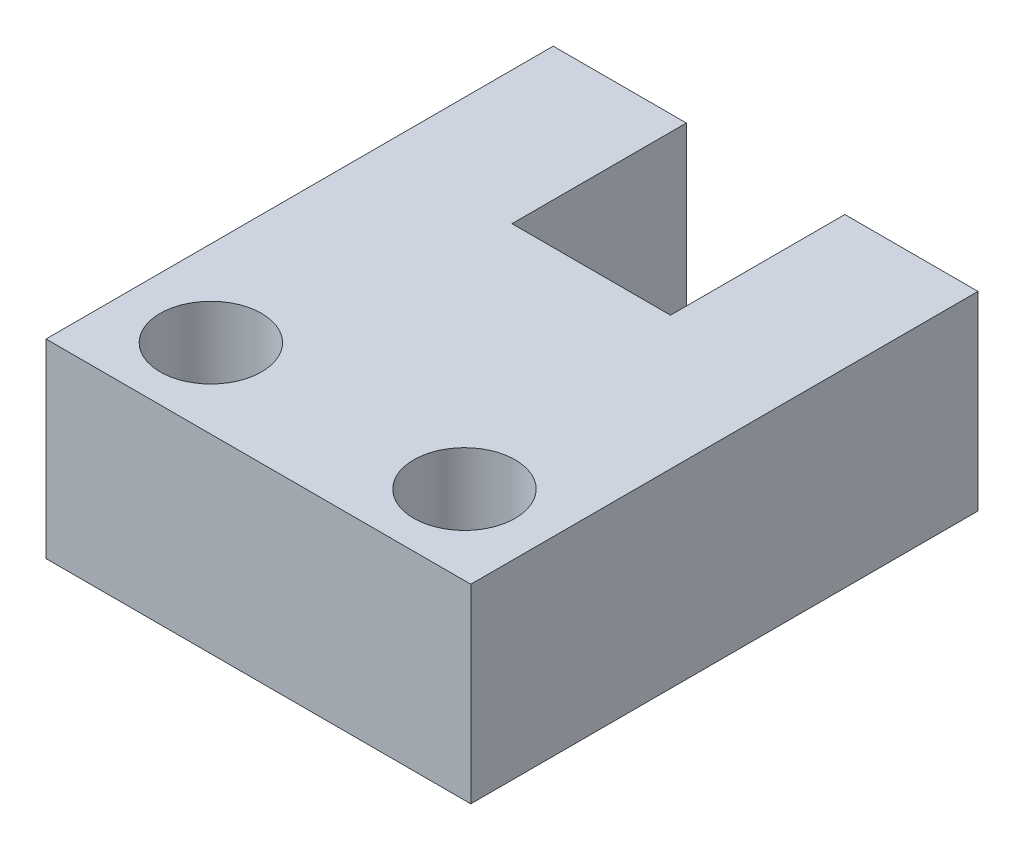
SolidWorks part; units mm, degrees
ref_plane "Front Plane" through (0, 0, 0) normal (0, 0, 1) x (1, 0, 0)
ref_plane "Top Plane" through (0, 0, 0) normal (0, 1, 0) x (1, 0, 0)
ref_plane "Right Plane" through (0, 0, 0) normal (1, 0, 0) x (0, 0, -1)
other "Configuration Table"
sketch "草图1" plane through (0, 0, 0) normal (0, 1, 0) x (1, 0, 0)
  line L0 (0, 8) -> (0, -5.5) construction
  line L1 (-6.7, 8) -> (-2.5, 8)
  line L2 (-6.7, 8) -> (-6.7, -8)
  line L3 (-6.7, -8) -> (6.7, -8)
  line L4 (6.7, 8) -> (6.7, -8)
  line L5 (-6.7, 8) -> (6.7, -8) construction
  line L6 (-6.7, -8) -> (6.7, 8) construction
  line L7 (0, -5.5) -> (4, -5.5) construction
  line L8 (2.5, 8) -> (2.5, 2.5)
  line L9 (2.5, 2.5) -> (-2.5, 2.5)
  line L10 (-2.5, 8) -> (-2.5, 2.5)
  line L11 (2.5, 8) -> (6.7, 8)
  circle A0 centre (4, -5.5) radius 1.6
  circle A1 centre (-4, -5.5) radius 1.6
  point P0 (0, 0)
  point P16 (0, 2.5)
extrude "凸台-拉伸1" add sketch "草图1" along normal blind 6
